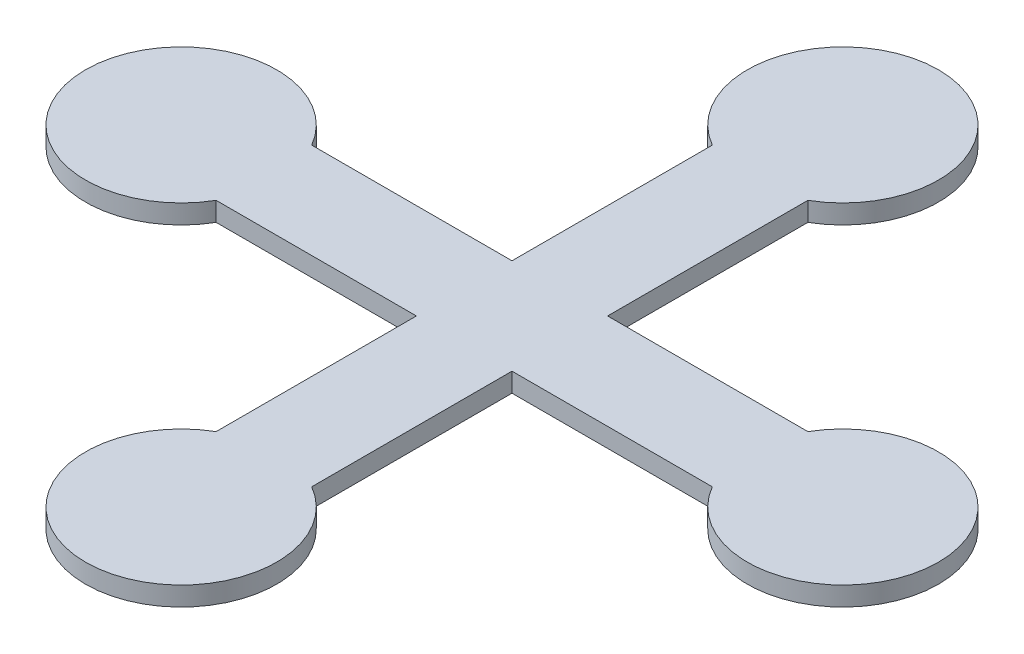
SolidWorks part; units mm, degrees
ref_plane "Front Plane" through (0, 0, 0) normal (0, 0, 1) x (1, 0, 0)
ref_plane "Top Plane" through (0, 0, 0) normal (0, 1, 0) x (1, 0, 0)
ref_plane "Right Plane" through (0, 0, 0) normal (1, 0, 0) x (0, 0, -1)
sketch "Sketch1" plane through (0, 0, 0) normal (0, 1, 0) x (1, 0, 0)
  line L0 (0, 0.8653) -> (0, -1.1347) construction
  line L1 (-1, 0) -> (1, 0) construction
  line L3 (-0.125, 0) -> (0.125, 0) construction
  line L4 (-0.125, 0.125) -> (-0.125, 0.6488)
  line L6 (0.125, 0.125) -> (0.125, 0.6488)
  line L7 (0.125, -0.125) -> (0.6488, -0.125)
  line L8 (0.125, 0.125) -> (0.6488, 0.125)
  line L9 (0, 0.125) -> (0, -0.125) construction
  line L10 (-0.125, -0.125) -> (-0.125, -0.6488)
  line L11 (0.125, -0.125) -> (0.125, -0.6488)
  line L12 (0.125, 0) -> (-0.125, 0) construction
  line L13 (-0.125, 0.125) -> (-0.6488, 0.125)
  line L14 (-0.125, -0.125) -> (-0.6488, -0.125)
  line L15 (0, -0.125) -> (0, 0.125) construction
  arc A0 (0.125, 0.6488) -> (-0.125, 0.6488) centre (0, 0.8653) ccw
  arc A1 (0.6488, -0.125) -> (0.6488, 0.125) centre (0.8653, 0) ccw
  arc A2 (-0.125, -0.6488) -> (0.125, -0.6488) centre (0, -0.8653) ccw
  arc A3 (-0.6488, 0.125) -> (-0.6488, -0.125) centre (-0.8653, 0) ccw
  point P18 (0, 0)
  point P27 (0, 0)
  dimension "D1" = 0.25
  dimension "D2" = 0.25
  dimension "D3" = 0.6488
  dimension "D4" = 2
  dimension "D5" = 4
extrude "Boss-Extrude1" add sketch "Sketch1" along normal blind 0.05
